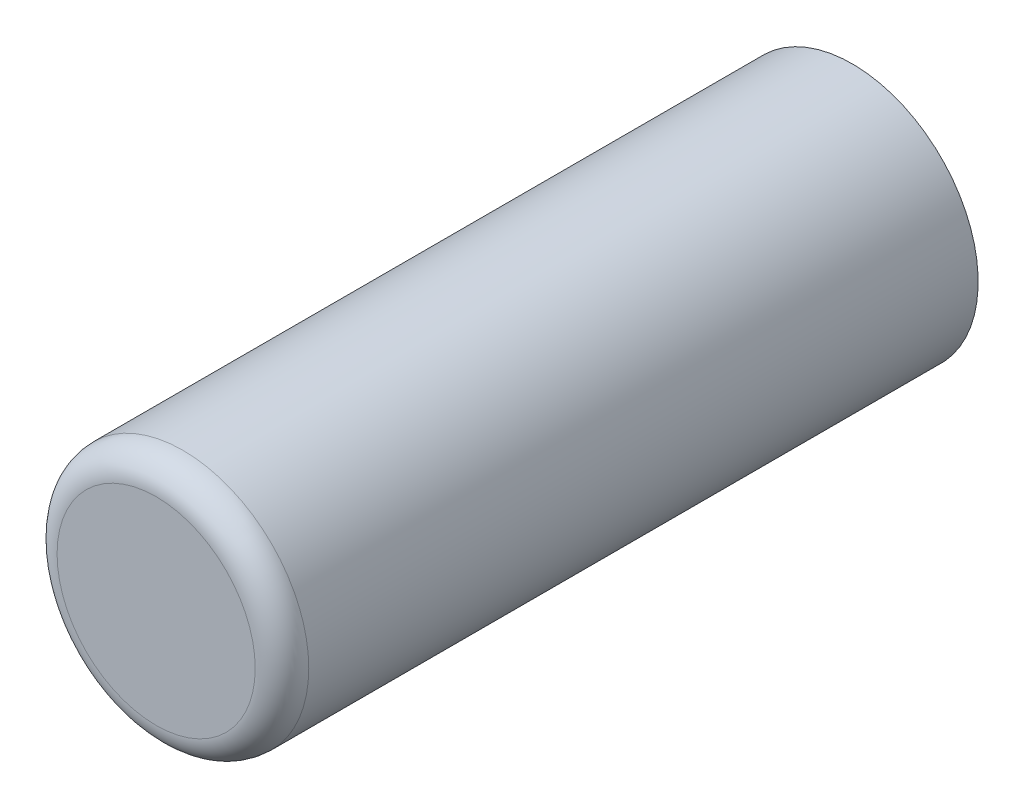
SolidWorks part; units mm, degrees
ref_plane "Ebene vorne" through (0, 0, 0) normal (0, 0, 1) x (1, 0, 0)
ref_plane "Ebene oben" through (0, 0, 0) normal (0, 1, 0) x (1, 0, 0)
ref_plane "Ebene rechts" through (0, 0, 0) normal (1, 0, 0) x (0, 0, -1)
sketch "Skizze1" plane through (0, 0, 0) normal (0, 0, 1) x (1, 0, 0)
  circle A0 centre (0, 0) radius 2.35
  dimension "D1" = 4.7
extrude "Aufsatz-Linear austragen1" add sketch "Skizze1" along normal blind 13
fillet "Verrundung1" radius 0.5 1 edges at (2.35, 0, 13)
